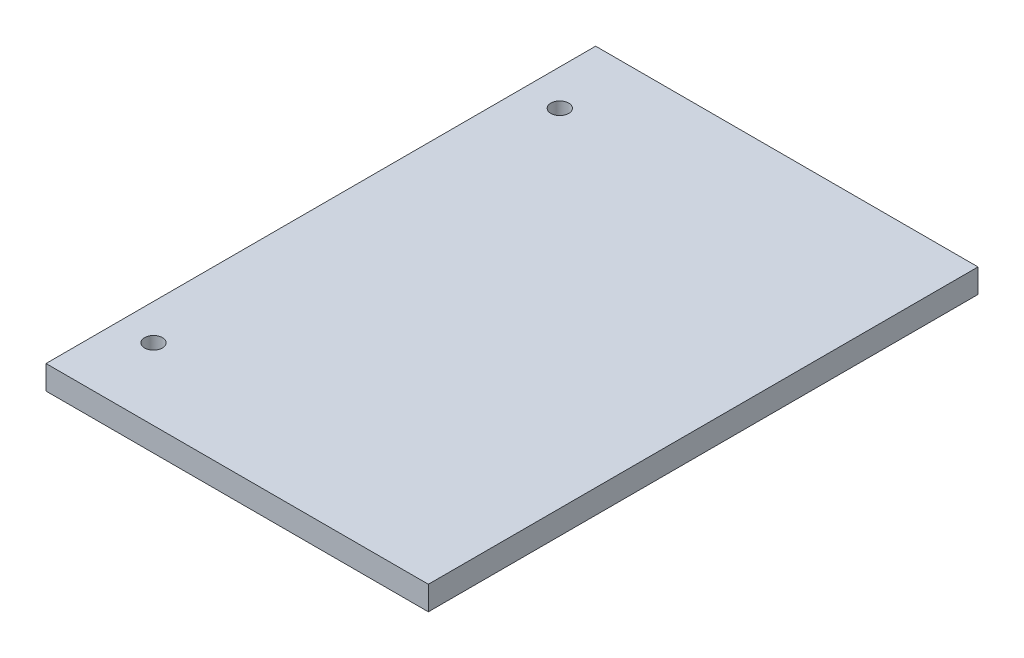
SolidWorks part; units mm, degrees
material "Pine"
ref_plane "Front Plane" through (0, 0, 0) normal (0, 0, 1) x (1, 0, 0)
ref_plane "Top Plane" through (0, 0, 0) normal (0, 1, 0) x (1, 0, 0)
ref_plane "Right Plane" through (0, 0, 0) normal (1, 0, 0) x (0, 0, -1)
sketch "Sketch1" plane through (0, 0, 0) normal (0, 1, 0) x (1, 0, 0)
  line L1 (0, 0) -> (101.6, 0)
  line L2 (0, 0) -> (0, -146.05)
  line L3 (0, -146.05) -> (101.6, -146.05)
  line L4 (101.6, 0) -> (101.6, -146.05)
  point P5 (0, 0)
  dimension "D1" = 101.6
  dimension "D2" = 146.05
extrude "Boss-Extrude1" add sketch "Sketch1" along normal blind 6.35
sketch "Sketch2" plane through (0, 6.35, 0) normal (0, 1, 0) x (1, 0, 0)
  circle A0 centre (9.525, -19.05) radius 2.3813
  circle A1 centre (9.525, -127) radius 2.3813
  dimension "D4" = 4.7625
  dimension "D5" = 4.7625
extrude "Cut-Extrude1" cut sketch "Sketch2" against normal blind 6.35
